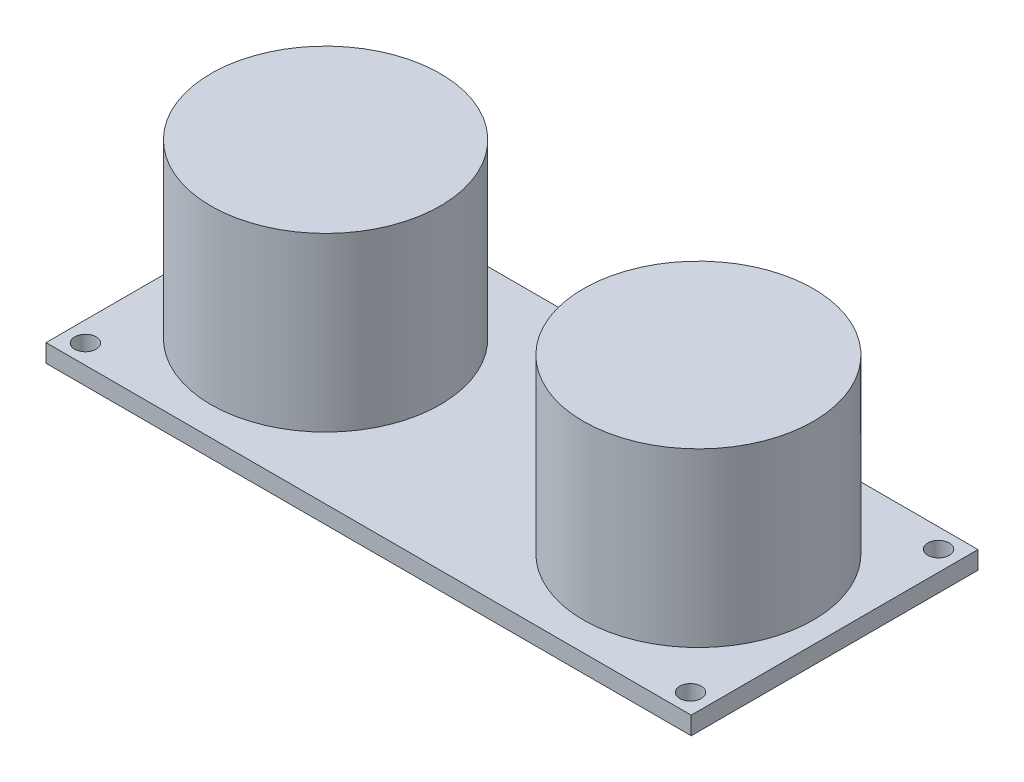
SolidWorks part; units mm, degrees
ref_plane "Front Plane" through (0, 0, 0) normal (0, 0, 1) x (1, 0, 0)
ref_plane "Top Plane" through (0, 0, 0) normal (0, 1, 0) x (1, 0, 0)
ref_plane "Right Plane" through (0, 0, 0) normal (1, 0, 0) x (0, 0, -1)
sketch "Sketch1" plane through (0, 0, 0) normal (0, 1, 0) x (1, 0, 0)
  line L0 (0, -20) -> (0, -18.65) construction
  line L1 (0, 0) -> (45, 0)
  line L2 (0, 0) -> (0, -20)
  line L3 (0, -20) -> (45, -20)
  line L4 (45, 0) -> (45, -20)
  line L5 (0, -18.65) -> (1.4, -18.65) construction
  line L6 (1.4, -18.65) -> (1.4, -19.4) construction
  circle A1 centre (1.4, -18.65) radius 0.75
  circle A2 centre (1.4, -1.35) radius 0.75
  circle A3 centre (43.6, -18.65) radius 0.75
  circle A4 centre (43.6, -1.35) radius 0.75
  dimension "D1" = 20
  dimension "D2" = 45
  dimension "D3" = 1.35
  dimension "D4" = 1.4
  dimension "D5" = 0.75
extrude "Boss-Extrude1" add sketch "Sketch1" along normal blind 1.25
sketch "Sketch3" plane through (0, 1.25, 0) normal (0, 1, 0) x (1, 0, 0)
  line L0 (0, -10) -> (9.5, -10) construction
  line L1 (0, 0) -> (0, -20) construction
  line L2 (9.5, -10) -> (17.5, -10) construction
  line L3 (17.5, -10) -> (27.5, -10) construction
  line L4 (27.5, -10) -> (35.5, -10) construction
  line L5 (35.5, -10) -> (45, -10) construction
  line L7 (45, -20) -> (45, 0) construction
  circle A0 centre (9.5, -10) radius 8
  circle A1 centre (35.5, -10) radius 8
  dimension "D1" = 9.5
  dimension "D2" = 8
  dimension "D3" = 10
  dimension "D4" = 8
extrude "Boss-Extrude2" add sketch "Sketch3" along normal blind 12 contours A0
sketch "Sketch4" plane through (0, 1.25, 0) normal (0, 1, 0) x (1, 0, 0)
  circle A0 centre (35.5, -10) radius 8.0181
extrude "Boss-Extrude3" add sketch "Sketch4" along normal blind 12
